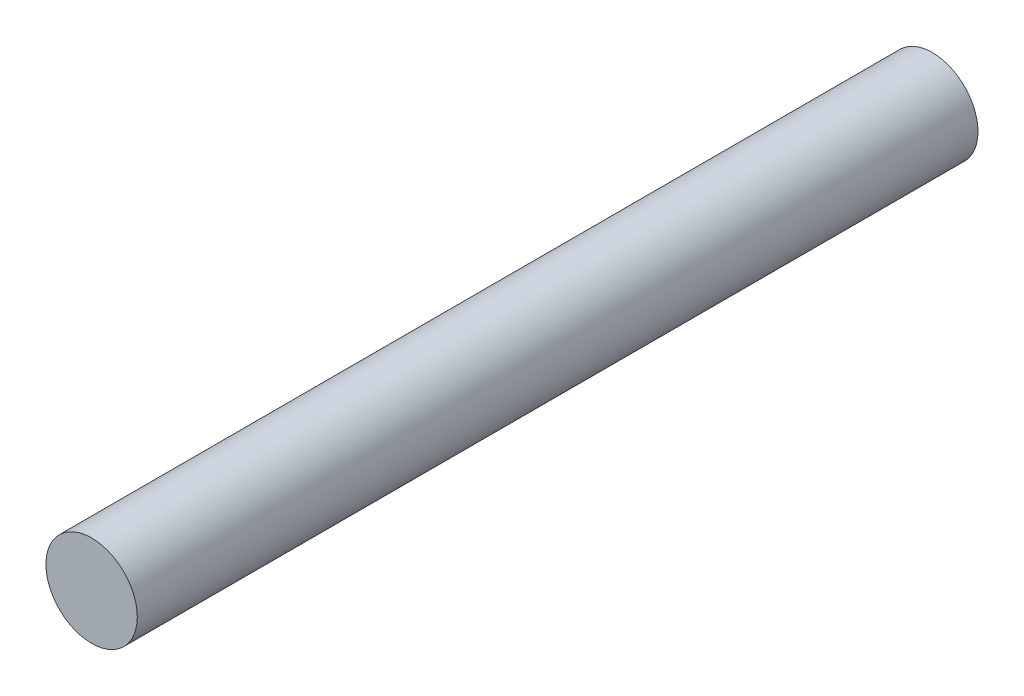
SolidWorks part; units mm, degrees
material "6061-T6 (SS)"
ref_plane "Front Plane" through (0, 0, 0) normal (0, 0, 1) x (1, 0, 0)
ref_plane "Top Plane" through (0, 0, 0) normal (0, 1, 0) x (1, 0, 0)
ref_plane "Right Plane" through (0, 0, 0) normal (1, 0, 0) x (0, 0, -1)
sketch "Body sketch" plane through (0, 0, 0) normal (0, 0, 1) x (1, 0, 0)
  circle A0 centre (0, 0) radius 2.5
extrude "Body" add sketch "Body sketch" along normal blind 46
